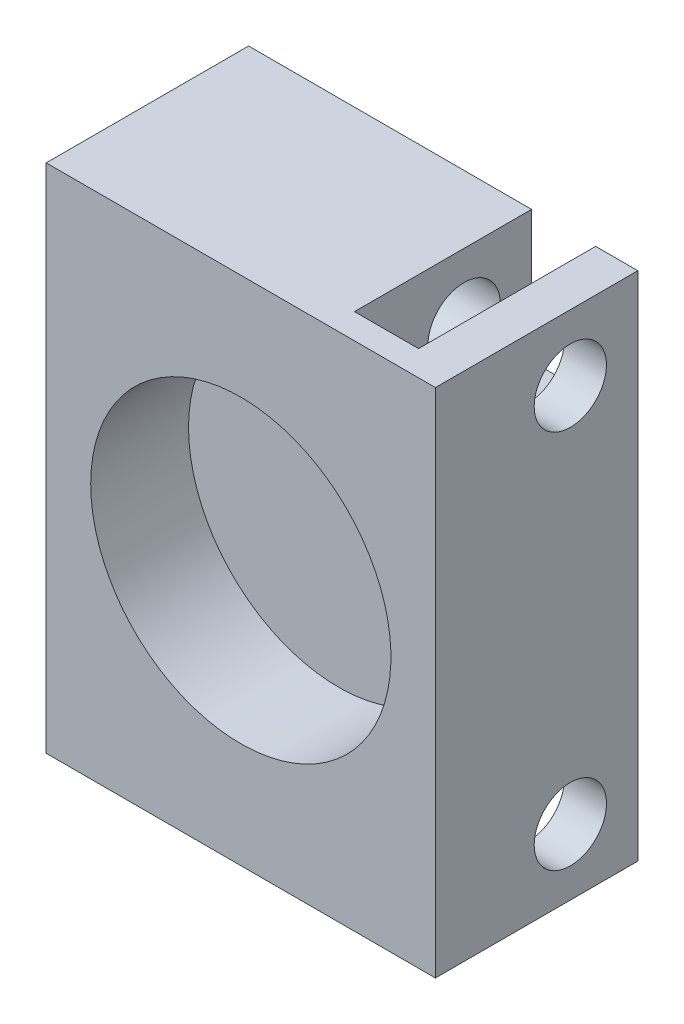
SolidWorks part; units mm, degrees
ref_plane "Front Plane" through (0, 0, 0) normal (0, 0, 1) x (1, 0, 0)
ref_plane "Top Plane" through (0, 0, 0) normal (0, 1, 0) x (1, 0, 0)
ref_plane "Right Plane" through (0, 0, 0) normal (1, 0, 0) x (0, 0, -1)
sketch "Sketch1" plane through (0, 0, 0) normal (0, 0, 1) x (1, 0, 0)
  line L1 (-14.6532, -19.252) -> (14.6532, -19.252)
  line L2 (-14.6532, -19.252) -> (-14.6532, 19.252)
  line L3 (-14.6532, 19.252) -> (14.6532, 19.252)
  line L4 (14.6532, -19.252) -> (14.6532, 19.252)
  line L5 (-14.6532, -19.252) -> (14.6532, 19.252) construction
  line L6 (-14.6532, 19.252) -> (14.6532, -19.252) construction
  circle A0 centre (0, 0) radius 11.303
  point P0 (0, 0)
  dimension "D1" = 22.606
extrude "Boss-Extrude1" add sketch "Sketch1" along normal blind 15.24
sketch "Sketch3" plane through (0, 0, 0) normal (0, 0, -1) x (-1, 0, 0)
  line L0 (8.2924, 19.252) -> (8.2924, 13) construction
  line L1 (-14.6532, 19.252) -> (14.6532, 19.252) construction
sketch "Sketch4" plane through (0, 0, 0) normal (0, 0, -1) x (-1, 0, 0)
  line L1 (-11.4782, 19.252) -> (-6.6522, 19.252)
  line L2 (-11.4782, 19.252) -> (-11.4782, 9.346)
  line L3 (-11.4782, 9.346) -> (-6.6522, 9.346)
  line L4 (-6.6522, 19.252) -> (-6.6522, 9.346)
  line L5 (-14.6532, -19.252) -> (-14.6532, 19.252) construction
  line L6 (-11.4782, 14.299) -> (-15.8356, 14.299) construction
  line L7 (-14.6532, 19.252) -> (14.6532, 19.252) construction
  dimension "D1" = 9.906
  dimension "D2" = 4.953
  dimension "D3" = 3.175
  dimension "D4" = 4.826
extrude "Cut-Extrude1" cut sketch "Sketch4" against normal blind 13.335
sketch "Sketch5" plane through (0, 0, 0) normal (0, 0, -1) x (-1, 0, 0)
  circle A0 centre (0, 0) radius 11.303 construction
  circle A1 centre (0, 0) radius 11.303
extrude "Boss-Extrude3" add sketch "Sketch5" against normal blind 7.874
sketch "Sketch6" plane through (-14.6532, 0, 0) normal (-1, 0, 0) x (0, 0, 1)
  line L0 (0, 19.252) -> (0, -19.252) construction
  circle A0 centre (5.08, 14.299) radius 2.7218
  dimension "D1" = 5.4435
  dimension "D2" = 5.08
extrude "Cut-Extrude2" cut sketch "Sketch6" against normal blind 31.75
mirror "Mirror1" about plane through (0, 0, 0) normal (0, 1, 0) of "Cut-Extrude2", "Cut-Extrude1"
